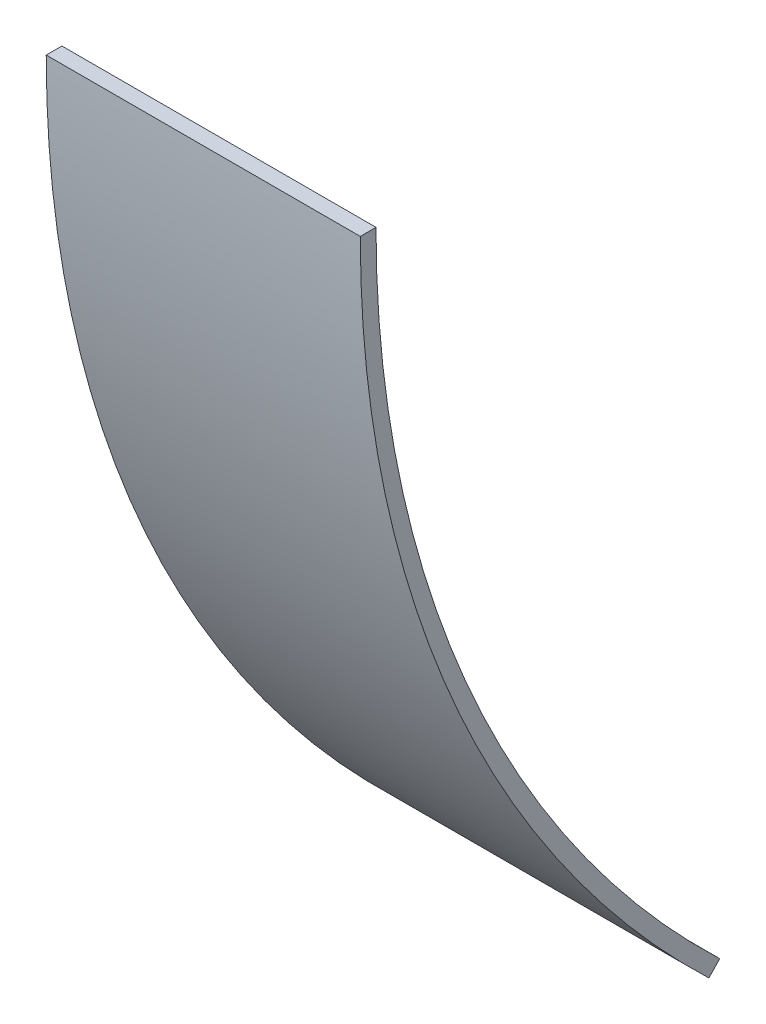
SolidWorks part; units mm, degrees
ref_plane "Front Plane" through (0, 0, 0) normal (0, 0, 1) x (1, 0, 0)
ref_plane "Top Plane" through (0, 0, 0) normal (0, 1, 0) x (1, 0, 0)
ref_plane "Right Plane" through (0, 0, 0) normal (1, 0, 0) x (0, 0, -1)
sketch "Sketch1" plane through (0, 0, 0) normal (1, 0, 0) x (0, 0, -1)
  line L0 (0, 0) -> (0, 117.9507) construction
  arc A0 (0, 0) -> (70.4863, -165.1) centre (228.6, 0) ccw
  dimension "D1" = 228.6
  dimension "D2" = 165.1
extrude "Extrude-Thin1" add sketch "Sketch1" along normal mid plane 63.5 thin thin type one direction reverse wall 3.175
